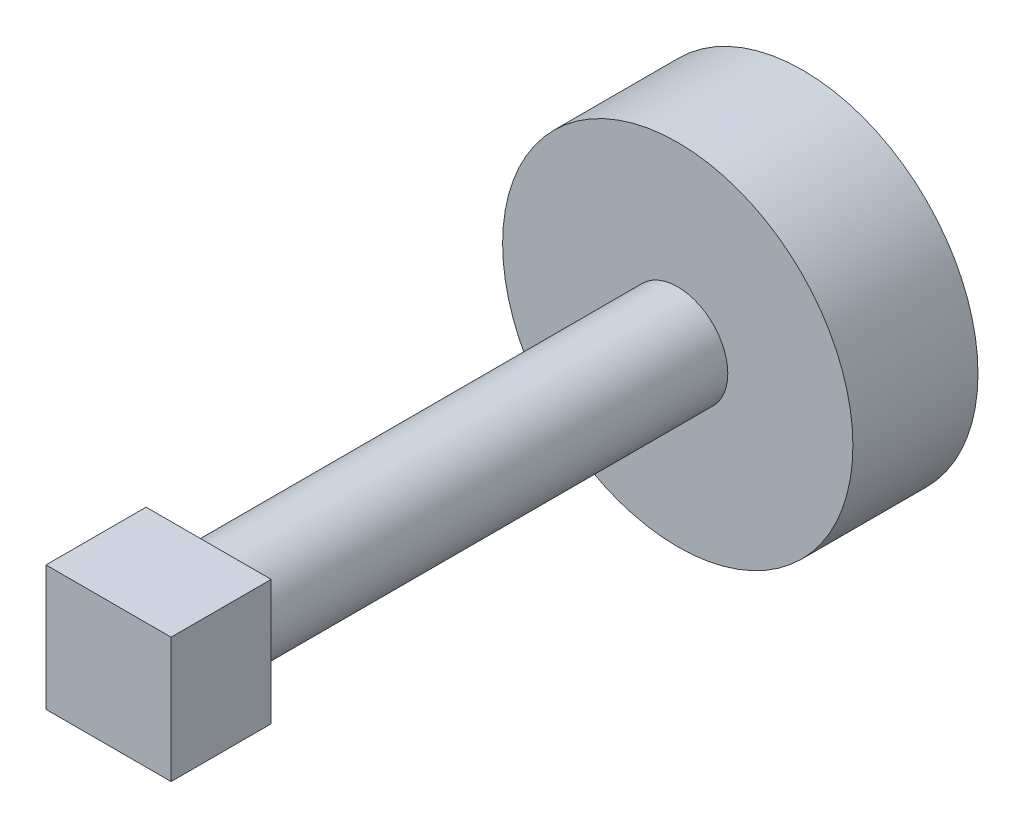
SolidWorks part; units mm, degrees
ref_plane "Front Plane" through (0, 0, 0) normal (0, 0, 1) x (1, 0, 0)
ref_plane "Top Plane" through (0, 0, 0) normal (0, 1, 0) x (1, 0, 0)
ref_plane "Right Plane" through (0, 0, 0) normal (1, 0, 0) x (0, 0, -1)
sketch "Sketch1" plane through (0, 0, 0) normal (0, 0, 1) x (1, 0, 0)
  circle A0 centre (0, 0) radius 14
  circle A1 centre (0, 0) radius 10
  circle A2 centre (0, 0) radius 5.5
extrude "Boss-Extrude1" add sketch "Sketch1" along normal blind 10 contours A0
sketch "Sketch2" plane through (0, 0, 0) normal (0, 0, -1) x (-1, 0, 0)
  circle A0 centre (0, 0) radius 2.25
extrude "Cut-Extrude1" cut sketch "Sketch2" against normal blind 5
sketch "Sketch3" plane through (0, 0, 0) normal (0, 0, -1) x (-1, 0, 0)
  circle A0 centre (0, 0) radius 5
extrude "Cut-Extrude2" cut sketch "Sketch3" against normal blind 1.8
sketch "Sketch11" plane through (0, 0, 10) normal (0, 0, 1) x (1, 0, 0)
  circle A0 centre (0, 0) radius 4
  point P0 (0, 0)
extrude "Boss-Extrude2" add sketch "Sketch11" along normal blind 37.5
sketch "Sketch12" plane through (0, 0, 47.5) normal (0, 0, 1) x (1, 0, 0)
  line L1 (-5, -5) -> (5, -5)
  line L2 (-5, -5) -> (-5, 5)
  line L3 (-5, 5) -> (5, 5)
  line L4 (5, -5) -> (5, 5)
  line L5 (-5, -5) -> (5, 5) construction
  line L6 (-5, 5) -> (5, -5) construction
  point P0 (0, 0)
  point P6 (-94.1203, 49.6619)
  dimension "D1" = 10
  dimension "10" = 10
extrude "Boss-Extrude3" add sketch "Sketch12" along normal blind 8
